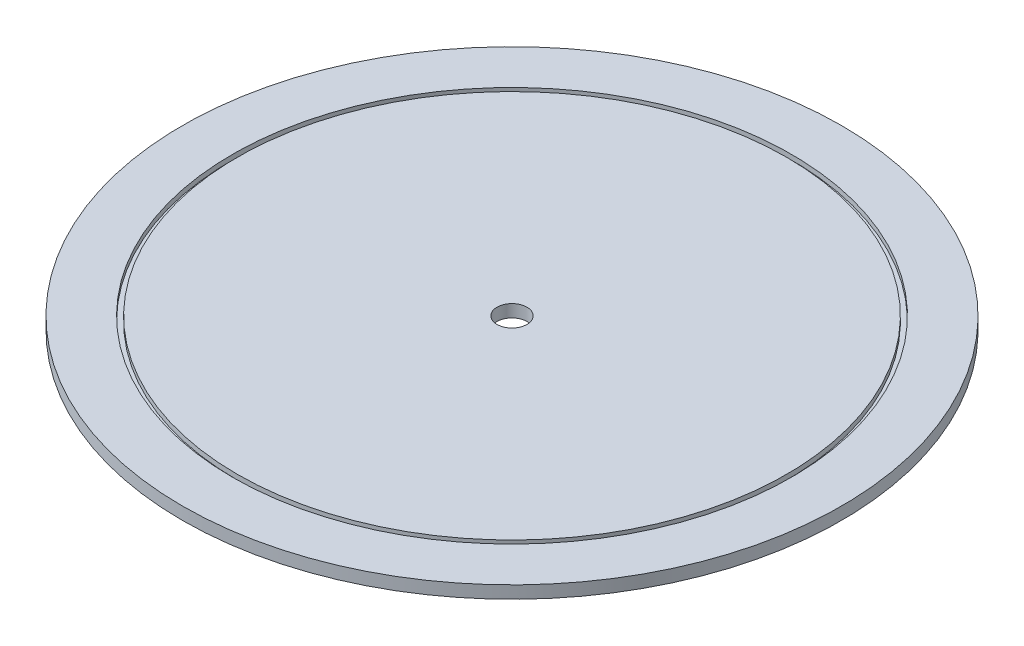
SolidWorks part; units mm, degrees
ref_plane "Front Plane" through (0, 0, 0) normal (0, 0, 1) x (1, 0, 0)
ref_plane "Top Plane" through (0, 0, 0) normal (0, 1, 0) x (1, 0, 0)
ref_plane "Right Plane" through (0, 0, 0) normal (1, 0, 0) x (0, 0, -1)
sketch "Sketch1" plane through (0, 0, 0) normal (0, 1, 0) x (1, 0, 0)
  circle A0 centre (0, 0) radius 132
extrude "Boss-Extrude1" add sketch "Sketch1" along normal blind 5
sketch "Sketch2" plane through (0, 5, 0) normal (0, 1, 0) x (1, 0, 0)
  circle A0 centre (0, 0) radius 110
  circle A1 centre (0, 0) radius 112
extrude "Cut-Extrude1" cut sketch "Sketch2" against normal blind 2
sketch "Sketch3" plane through (0, 5, 0) normal (0, 1, 0) x (1, 0, 0)
  circle A0 centre (0, 0) radius 6
extrude "Cut-Extrude2" cut sketch "Sketch3" against normal blind 22
